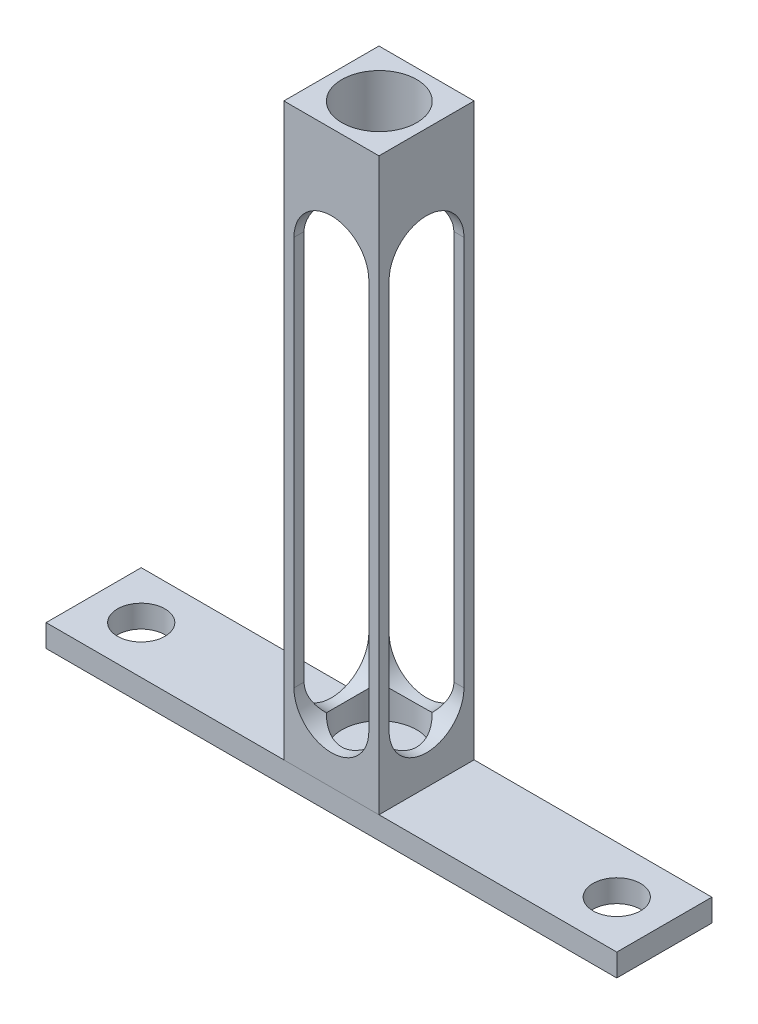
SolidWorks part; units mm, degrees
ref_plane "Front" through (0, 0, 0) normal (0, 0, 1) x (1, 0, 0)
ref_plane "Top" through (0, 0, 0) normal (0, 1, 0) x (1, 0, 0)
ref_plane "Right" through (0, 0, 0) normal (1, 0, 0) x (0, 0, -1)
other "Center of Mass"
sketch "Sketch1" plane through (0, 0, 0) normal (0, 0, 1) x (1, 0, 0)
  line L1 (0, 0) -> (12.7, 0)
  line L2 (0, 0) -> (0, 76.2)
  line L3 (0, 76.2) -> (12.7, 76.2)
  line L4 (12.7, 0) -> (12.7, 76.2)
  dimension "D1" = 76.2
  dimension "D2" = 12.7
extrude "Boss-Extrude1" add sketch "Sketch1" along normal blind 12.7
ref_point "Point1"
sketch "Sketch4" plane through (0, 0, 0) normal (0, -1, 0) x (-1, 0, 0)
  line L1 (31.7487, 0.0034) -> (-44.4513, 0.0034)
  line L2 (31.7487, 0.0034) -> (31.7487, -12.6966)
  line L3 (31.7487, -12.6966) -> (-44.4513, -12.6966)
  line L4 (-44.4513, 0.0034) -> (-44.4513, -12.6966)
  line L5 (31.7487, 0.0034) -> (-44.4513, -12.6966) construction
  line L6 (31.7487, -12.6966) -> (-44.4513, 0.0034) construction
  point P0 (-6.3513, -6.3466)
  dimension "D1" = 12.7
  dimension "D2" = 76.2
extrude "Boss-Extrude3" add sketch "Sketch4" along normal blind 3
sketch "Sketch12" plane through (0, 0, 12.7) normal (0, 0, 1) x (1, 0, 0)
  line L0 (6.35, 9) -> (6.35, 61.1) construction
  line L1 (1.35, 9) -> (1.35, 61.1)
  line L2 (11.35, 9) -> (11.35, 61.1)
  line L3 (44.4513, -3) -> (-31.7487, -3) construction
  line L4 (12.7, 0) -> (12.7, 76.2) construction
  arc A0 (1.35, 9) -> (11.35, 9) centre (6.35, 9) ccw
  arc A1 (11.35, 61.1) -> (1.35, 61.1) centre (6.35, 61.1) ccw
  point P2 (6.35, 35.05)
  dimension "D1" = 12
  dimension "D2" = 6.35
extrude "Cut-Extrude5" cut sketch "Sketch12" against normal blind 12.7
sketch "Sketch13" plane through (12.7, 0, 0) normal (1, 0, 0) x (0, 0, -1)
  line L0 (-6.35, 9) -> (-6.35, 61.1) construction
  line L1 (-11.35, 9) -> (-11.35, 61.1)
  line L2 (-1.35, 9) -> (-1.35, 61.1)
  line L3 (0.0034, -3) -> (-12.6966, -3) construction
  line L4 (0, 0) -> (0, 76.2) construction
  arc A0 (-11.35, 9) -> (-1.35, 9) centre (-6.35, 9) ccw
  arc A1 (-1.35, 61.1) -> (-11.35, 61.1) centre (-6.35, 61.1) ccw
  point P2 (-6.35, 35.05)
  point P7 (-6.3466, -3)
  dimension "D1" = 12
  dimension "D2" = 6.35
extrude "Cut-Extrude6" cut sketch "Sketch13" against normal blind 12.7
sketch "Sketch16" plane through (0, 76.2, 0) normal (0, 1, 0) x (1, 0, 0)
  circle A0 centre (6.3943, -6.3483) radius 5
extrude "Cut-Extrude8" cut sketch "Sketch16" against normal blind 75.2
sketch "Sketch17" plane through (0, 0, 0) normal (0, 1, 0) x (1, 0, 0)
  line L0 (-31.7487, 0.0034) -> (44.4513, 0.0034) construction
  line L1 (0, -12.6966) -> (-31.7487, -12.6966) construction
  circle A0 centre (-25.3987, -6.3466) radius 3.175
  point P2 (6.3513, 0.0034)
  dimension "D2" = 31.75
  dimension "D1" = 6.35
extrude "Cut-Extrude9" cut sketch "Sketch17" against normal blind 3
sketch "Sketch18" plane through (0, 0, 0) normal (0, 1, 0) x (1, 0, 0)
  line L0 (-31.7487, 0.0034) -> (44.4513, 0.0034) construction
  line L6 (12.7, -12.7) -> (0, -12.7) construction
  circle A0 centre (38.1, -6.3466) radius 3.175
  point P4 (6.35, -12.7)
  dimension "D1" = 6.35
  dimension "D2" = 31.75
extrude "Cut-Extrude10" cut sketch "Sketch18" against normal blind 3
